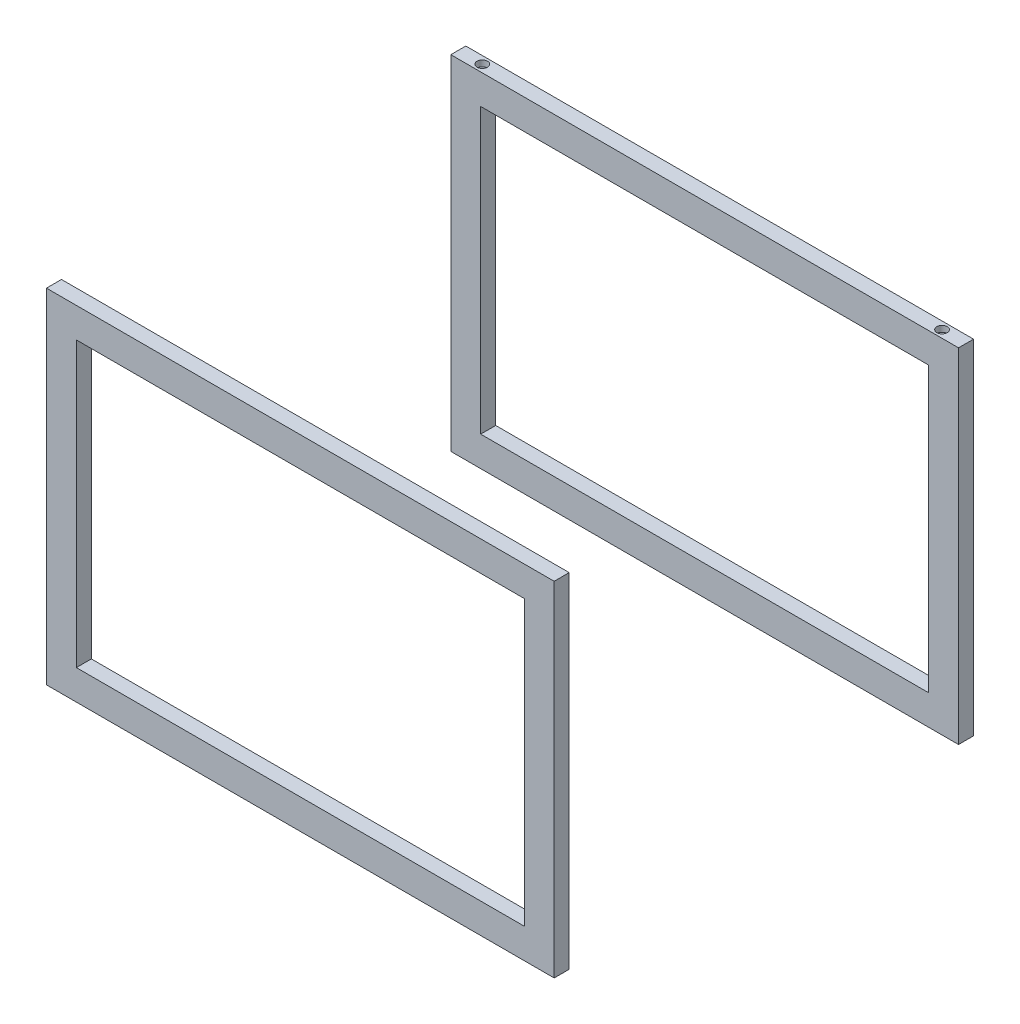
SolidWorks part; units mm, degrees
ref_plane "Plan de face" through (0, 0, 0) normal (0, 0, 1) x (1, 0, 0)
ref_plane "Plan de dessus" through (0, 0, 0) normal (0, 1, 0) x (1, 0, 0)
ref_plane "Plan de droite" through (0, 0, 0) normal (1, 0, 0) x (0, 0, -1)
sketch "Esquisse8" plane through (0, 0, 0) normal (0, 0, 1) x (1, 0, 0)
  line L1 (0, 0) -> (1695, 0)
  line L2 (0, 0) -> (0, 1147)
  line L3 (0, 1147) -> (1695, 1147)
  line L4 (1695, 0) -> (1695, 1147)
  line L5 (99.81, 1047.19) -> (1595.19, 1047.19)
  line L6 (99.81, 1047.19) -> (99.81, 589.81)
  line L7 (99.81, 589.81) -> (1595.19, 589.81)
  line L8 (1595.19, 1047.19) -> (1595.19, 589.81)
  line L9 (99.81, 203) -> (689.81, 203) construction
  line L10 (99.81, 203) -> (99.81, 99.81) construction
  line L11 (99.81, 99.81) -> (689.81, 99.81) construction
  line L12 (689.81, 203) -> (689.81, 99.81) construction
  line L21 (789.62, 203) -> (1215, 203) construction
  line L22 (789.62, 203) -> (789.62, 99.81) construction
  line L23 (789.62, 99.81) -> (1215, 99.81) construction
  line L24 (1215, 203) -> (1215, 99.81) construction
  line L25 (1314.81, 203) -> (1595.19, 203) construction
  line L26 (1314.81, 203) -> (1314.81, 99.81) construction
  line L27 (1314.81, 99.81) -> (1595.19, 99.81) construction
  line L28 (1595.19, 203) -> (1595.19, 99.81) construction
  point P22 (1314.81, 151.405)
  dimension "D1" = 1695
  dimension "D2" = 1147
  dimension "D3" = 99.81
  dimension "D4" = 99.81
  dimension "D5" = 99.81
  dimension "D7" = 99.81
  dimension "D8" = 625
  dimension "D9" = 99.81
  dimension "D10" = 99.81
  dimension "D11" = 944
  dimension "D12" = 590
extrude "Boss.-Extru.8" add sketch "Esquisse8" along normal blind 50.13
ref_plane "Plan19" through (0, 0, 1400) normal (0, 0, -1) x (-1, 0, 0)
sketch "Esquisse9" plane through (0, 0, 1400) normal (0, 0, -1) x (-1, 0, 0)
  line L0 (-1215, 431.81) -> (-789.62, 431.81)
  line L1 (-1695, 1147) -> (0, 1147)
  line L2 (-1695, 1147) -> (-1695, 0)
  line L3 (-1695, 0) -> (0, 0)
  line L4 (0, 1147) -> (0, 0)
  line L5 (-1595.19, 1047.19) -> (-99.81, 1047.19)
  line L6 (-1595.19, 1047.19) -> (-1595.19, 589.81)
  line L7 (-1595.19, 589.81) -> (-99.81, 589.81)
  line L8 (-99.81, 1047.19) -> (-99.81, 589.81)
  line L9 (-1595.19, 490) -> (-1314.81, 490)
  line L10 (-1595.19, 490) -> (-1595.19, 99.81)
  line L11 (-1595.19, 99.81) -> (-1314.81, 99.81)
  line L12 (-1314.81, 490) -> (-1314.81, 99.81)
  line L13 (-1215, 490) -> (-789.62, 490)
  line L14 (-1215, 490) -> (-1215, 99.81)
  line L15 (-1215, 99.81) -> (-789.62, 99.81)
  line L16 (-789.62, 490) -> (-789.62, 99.81)
  line L17 (-689.81, 490) -> (-99.81, 490)
  line L18 (-689.81, 490) -> (-689.81, 99.81)
  line L19 (-689.81, 99.81) -> (-99.81, 99.81)
  line L20 (-99.81, 490) -> (-99.81, 99.81)
  dimension "D5" = 99.81
  dimension "D1" = 158
  dimension "D2" = 99.81
  dimension "D3" = 625
  dimension "D4" = 590
  dimension "D6" = 99.81
  dimension "D7" = 99.81
extrude "Boss.-Extru.9" add sketch "Esquisse9" along normal blind 50.13 separate body contours L16 L13 L14 L0 | L4 L1 L2 L3 L5 L8 L7 L6 L9 L12 L11 L10 L13 L16 L15 L14 L17 L20 L19 L18
sketch "Esquisse12" plane through (0, 0, 50.13) normal (0, 0, 1) x (1, 0, 0)
  line L1 (99.81, 589.81) -> (1595.19, 589.81)
  line L2 (99.81, 589.81) -> (99.81, 99.81)
  line L3 (99.81, 99.81) -> (1595.19, 99.81)
  line L4 (1595.19, 589.81) -> (1595.19, 99.81)
extrude "Enlèv. mat.-Extru.1" cut sketch "Esquisse12" against normal blind 50.13
sketch "Esquisse13" plane through (0, 0, 1400) normal (0, 0, 1) x (1, 0, 0)
  line L1 (99.81, 1047.19) -> (1595.19, 1047.19)
  line L2 (99.81, 1047.19) -> (99.81, 99.81)
  line L3 (99.81, 99.81) -> (1595.19, 99.81)
  line L4 (1595.19, 1047.19) -> (1595.19, 99.81)
extrude "Enlèv. mat.-Extru.2" cut sketch "Esquisse13" against normal up to surface (50.13 mm away) up to face at (1002.31, 265.81, 1349.87)
sketch "Esquisse14" plane through (0, 1147, 0) normal (0, 1, 0) x (1, 0, 0)
  line L0 (1695, -25.065) -> (847.5, -25.065) construction
  line L1 (1695, -50.13) -> (1695, 0) construction
  line L2 (847.5, 0) -> (847.5, -50.13) construction
  line L3 (1695, 0) -> (0, 0) construction
  line L4 (1695, -50.13) -> (0, -50.13) construction
  circle A0 centre (1615, -25.065) radius 17.5
  circle A1 centre (80, -25.065) radius 17.5
  point P6 (847.5, -25.065)
  dimension "D1" = 35
  dimension "D2" = 80
extrude "Enlèv. mat.-Extru.3" cut sketch "Esquisse14" against normal blind 20
equation "\"hauteur de barre\"= 99.81mm"
equation "\"largeur du barre\"= 50.13mm"
equation "\"longeur du barre\"= 1695mm"
equation "\"espacement entre deux barres\"=1147"
equation "\"D1@Esquisse8\"=\"longeur du barre\""
equation "\"D2@Esquisse8\"=\"espacement entre deux barres\""
equation "\"D3@Esquisse8\"=\"hauteur de barre\""
equation "\"D4@Esquisse8\"=\"hauteur de barre\""
equation "\"D5@Esquisse8\"=\"hauteur de barre\""
equation "\"D7@Esquisse8\"=\"hauteur de barre\""
equation "\"D8@Esquisse8\"=625"
equation "\"D9@Esquisse8\"=\"hauteur de barre\""
equation "\"D10@Esquisse8\"=\"hauteur de barre\""
equation "\"D1@Boss.-Extru.8\"=\"largeur du barre\""
equation "\"D1@Boss.-Extru.9\"=\"largeur du barre\""
equation "\"D2@Esquisse9\"=\"hauteur de barre\""
equation "\"D5@Esquisse9\"=\"hauteur de barre\""
equation "\"D6@Esquisse9\"=\"hauteur de barre\""
equation "\"D7@Esquisse9\"=\"hauteur de barre\""
